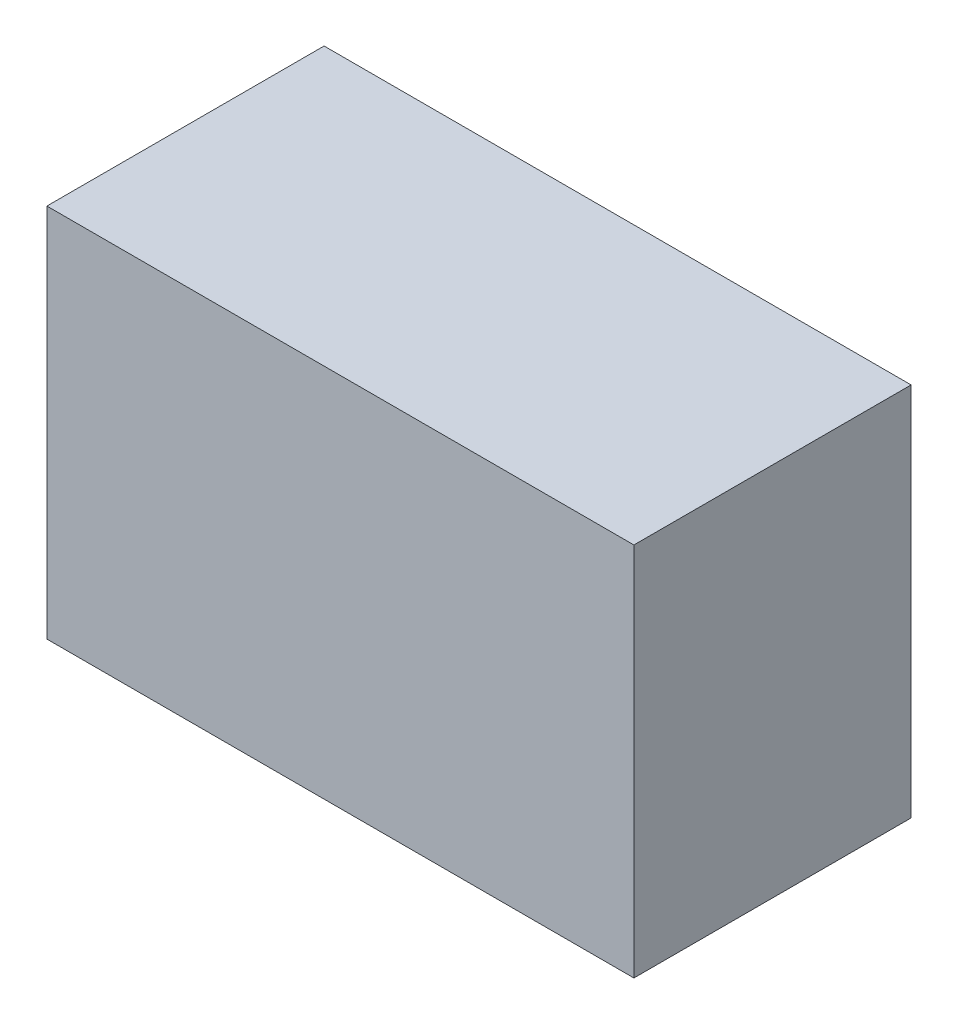
SolidWorks part; units mm, degrees
ref_plane "前视基准面" through (0, 0, 0) normal (0, 0, 1) x (1, 0, 0)
ref_plane "上视基准面" through (0, 0, 0) normal (0, 1, 0) x (1, 0, 0)
ref_plane "右视基准面" through (0, 0, 0) normal (1, 0, 0) x (0, 0, -1)
other "Configuration Table"
sketch "草图1" plane through (0, 0, 0) normal (0, 1, 0) x (1, 0, 0)
  line L1 (-36, -17) -> (36, -17)
  line L2 (-36, -17) -> (-36, 17)
  line L3 (-36, 17) -> (36, 17)
  line L4 (36, -17) -> (36, 17)
  line L5 (-36, -17) -> (36, 17) construction
  line L6 (-36, 17) -> (36, -17) construction
  point P0 (0, 0)
  dimension "D1" = 72
  dimension "D2" = 34
extrude "凸台-拉伸1" add sketch "草图1" along normal blind 46
